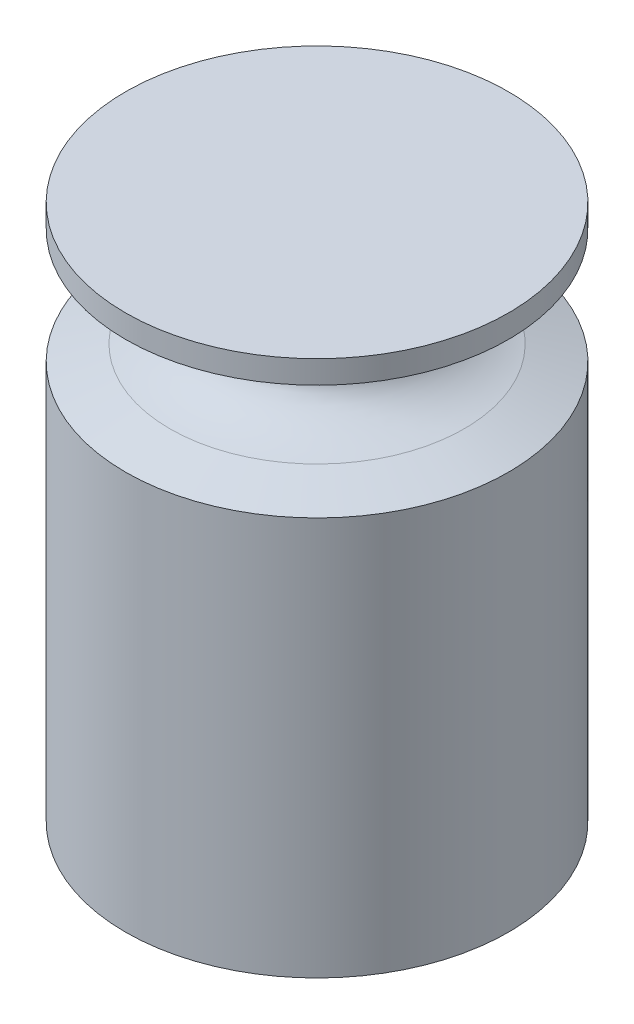
SolidWorks part; units mm, degrees
ref_plane "Front Plane" through (0, 0, 0) normal (0, 0, 1) x (1, 0, 0)
ref_plane "Top Plane" through (0, 0, 0) normal (0, 1, 0) x (1, 0, 0)
ref_plane "Right Plane" through (0, 0, 0) normal (1, 0, 0) x (0, 0, -1)
sketch "Sketch1" plane through (0, 0, 0) normal (0, 1, 0) x (1, 0, 0)
  circle A0 centre (0, 0) radius 25
  dimension "D1" = 50
extrude "Boss-Extrude1" add sketch "Sketch1" along normal blind 70
sketch "Sketch2" plane through (0, 0, 0) normal (0, 0, 1) x (1, 0, 0)
  line L0 (0, 70) -> (0, 0) construction
  line L1 (25, 70) -> (-25, 70) construction
  line L2 (0, 70) -> (-25, 70) construction
  line L3 (-25, 70) -> (-25, 67) construction
  line L4 (-25, 70) -> (-25, 0) construction
  line L5 (-25, 67) -> (-19.207, 65)
  line L6 (-19.207, 65) -> (-12.5, 65) construction
  line L7 (0, 0) -> (-25, 0) construction
  line L8 (27.5, 0) -> (-27.5, 0) construction
  line L9 (-25, 0) -> (-25, 52) construction
  line L10 (-25, 52) -> (-19.207, 54)
  line L11 (-19.207, 54) -> (-12.5, 54) construction
  line L12 (-12.5, 54) -> (-12.5, 65) construction
  line L13 (-25, 52) -> (-25, 67)
  spline S0 degree 3 poles (-19.207, 65) (-10.6277, 62.5133) (-9.9009, 56.4867) (-19.207, 54) knots 0 0 0 0 1 1 1 1
  dimension "D1" = 12.5
  dimension "D2" = 2
  dimension "D3" = 2
  dimension "D4" = 3
  dimension "D5" = 52
  dimension "D6" = 15
revolve "Cut-Revolve3" cut sketch "Sketch2" angle 360 about L0
sketch "Sketch3" plane through (0, 70, 0) normal (0, 1, 0) x (1, 0, 0)
  circle A0 centre (0, 0) radius 12.5
